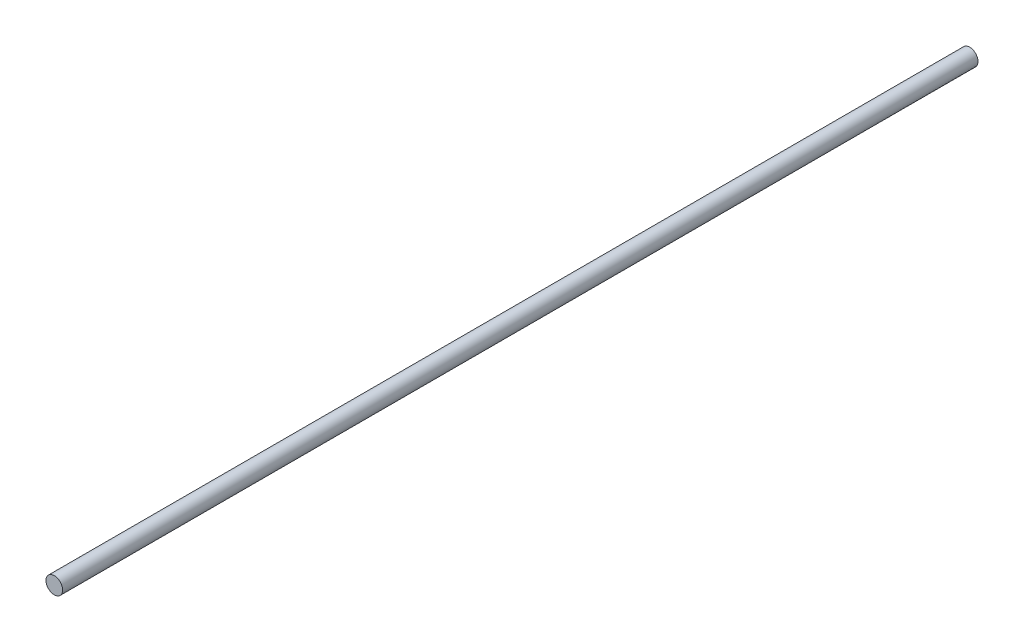
SolidWorks part; units mm, degrees
ref_plane "Front Plane" through (0, 0, 0) normal (0, 0, 1) x (1, 0, 0)
ref_plane "Top Plane" through (0, 0, 0) normal (0, 1, 0) x (1, 0, 0)
ref_plane "Right Plane" through (0, 0, 0) normal (1, 0, 0) x (0, 0, -1)
other "Configuration Table"
sketch "Sketch1" plane through (0, 0, 0) normal (0, 0, 1) x (1, 0, 0)
  circle A0 centre (0, 170) radius 6
extrude "KAP_tarak_mili_D12" add sketch "Sketch1" against normal blind 660 from offset 40 separate body
